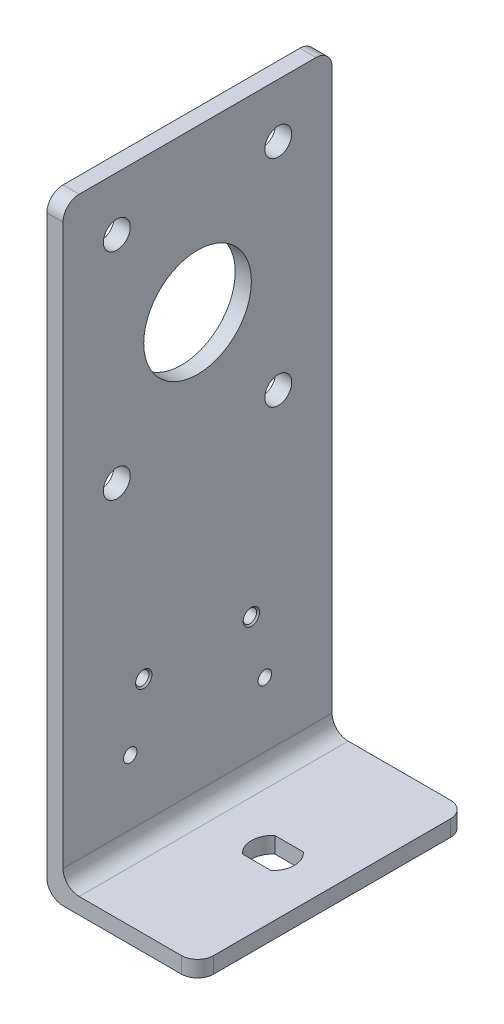
SolidWorks part; units mm, degrees
ref_plane "Front Plane" through (0, 0, 0) normal (0, 0, 1) x (1, 0, 0)
ref_plane "Top Plane" through (0, 0, 0) normal (0, 1, 0) x (1, 0, 0)
ref_plane "Right Plane" through (0, 0, 0) normal (1, 0, 0) x (0, 0, -1)
sketch "Sketch1" plane through (0, 0, 0) normal (0, 0, 1) x (1, 0, 0)
  line L0 (0, 110) -> (0, 0)
  line L1 (0, 0) -> (25, 0)
  dimension "D1" = 25
  dimension "D2" = 110
extrude "Extrude-Thin1" add sketch "Sketch1" along normal blind 50 thin
hole_wizard "Hole1" positions "3DSketch1" profile "Sketch2" legacy end condition through all
sketch3d "3DSketch1"
  line L0 (-3, 110, 50) -> (-3, 110, 0) construction
  line L1 (-3, 110, 0) -> (-3, -3, 0) construction
  point P0 (-3, 100, 10)
  point P2 (-3, 100, 40)
  point P4 (-3, 60, 40)
  point P6 (-3, 60, 10)
  dimension "D1" = 30
  dimension "D2" = 40
  dimension "D3" = 10
  dimension "D4" = 10
sketch "Sketch2" plane through (-3, 100, 10) normal (0, 1, 0) x (0, 0, 1)
  line L0 (0, 0) -> (0, 28)
  line L1 (0, 28) -> (2.5, 28)
  line L2 (2.5, 28) -> (2.5, 0)
  line L3 (2.5, 0) -> (0, 0)
  line L4 (0, 110) -> (0, -10) construction
  dimension "Diameter" = 5
  dimension "Depth" = 28
sketch "Sketch3" plane through (-3, 0, 0) normal (-1, 0, 0) x (0, 0, 1)
  line L0 (0, 110) -> (0, -3) construction
  line L1 (50, 110) -> (0, 110) construction
  circle A0 centre (25, 80) radius 10
  dimension "D3" = 20
  dimension "D1" = 25
  dimension "D2" = 30
extrude "Cut-Extrude1" cut sketch "Sketch3" against normal through all
hole_wizard "M3 Tapped Hole1" positions "3DSketch2" profile "Sketch4" tap size "M3" standard "ISO"
sketch3d "3DSketch2"
  line L0 (-3, 110, 0) -> (-3, -3, 0) construction
  line L1 (-3, 110, 50) -> (-3, 110, 0) construction
  point P0 (-3, 15, 12.5)
  point P2 (-3, 15, 37.5)
  dimension "D1" = 25
  dimension "D2" = 12.5
  dimension "D3" = 95
sketch "Sketch4" plane through (-3, 15, 12.5) normal (0, 1, 0) x (0, 0, 1)
  line L0 (0, 0) -> (0, 8.2511)
  line L1 (0, 8.2511) -> (1.25, 7.5)
  line L2 (1.25, 7.5) -> (1.25, 0.275)
  line L3 (1.25, 0.275) -> (1.525, 0)
  line L5 (1.525, 0) -> (0, 0)
  line L6 (-1.25, 0.275) -> (-1.525, 0) construction
  line L10 (0, 8.2511) -> (-1.25, 7.5) construction
  line L11 (0, -6.35) -> (0, 107.95) construction
  dimension "Tap Drill Dia." = 2.5
  dimension "Tap Drill Depth" = 7.5
  dimension "Near C'Sink Dia." = 3.05
  dimension "Near C'Sink Angle" = 90
  dimension "Drill Angle" = 118
cosmetic thread "Hole Thread1" parameters "D1"=3, "D2"=3
cosmetic thread "Hole Thread2" parameters "D1"=3, "D2"=3
sketch "Sketch5" plane through (0, -3, 0) normal (0, -1, 0) x (-1, 0, 0)
  line L0 (3, -50) -> (3, 0) construction
  line L1 (-11.3542, -22) -> (-16.6458, -22)
  line L2 (-11.3542, -28) -> (-16.6458, -28)
  line L3 (3, -50) -> (-25, -50) construction
  arc A0 (-11.3542, -28) -> (-11.3542, -22) centre (-14, -25) ccw
  arc A1 (-16.6458, -22) -> (-16.6458, -28) centre (-14, -25) ccw
  dimension "D1" = 4
  dimension "D3" = 6
  dimension "D4" = 17
  dimension "D5" = 22
extrude "Cut-Extrude2" cut sketch "Sketch5" against normal blind 10 contours L1 A1 L2 A0
fillet "Fillet1" radius 3 4 edges at (25, -1.5, 50) (25, -1.5, 0) (-1.5, 110, 0) (-1.5, 110, 50)
hole_wizard "M3 Tapped Hole2" positions "3DSketch3" profile "Sketch6" tap size "M3" standard "ISO"
sketch3d "3DSketch3"
  line L2 (0, 107, 0) -> (0, 0, 0) construction
  line L4 (0, 0, 50) -> (0, 0, 0) construction
  point P0 (0, 26, 35)
  point P2 (0, 26, 15)
  dimension "D1" = 20
  dimension "D2" = 15
  dimension "D3" = 26
sketch "Sketch6" plane through (0, 26, 35) normal (0, 1, 0) x (0, 0, -1)
  line L0 (0, 0) -> (0, 8.2511)
  line L1 (0, 8.2511) -> (1.25, 7.5)
  line L2 (1.25, 7.5) -> (1.25, 0.275)
  line L3 (1.25, 0.275) -> (1.525, 0)
  line L5 (1.525, 0) -> (0, 0)
  line L6 (-1.25, 0.275) -> (-1.525, 0) construction
  line L10 (0, 8.2511) -> (-1.25, 7.5) construction
  line L11 (0, -6.35) -> (0, 107.95) construction
  dimension "Tap Drill Dia." = 2.5
  dimension "Tap Drill Depth" = 7.5
  dimension "Near C'Sink Dia." = 3.05
  dimension "Near C'Sink Angle" = 90
  dimension "Drill Angle" = 118
cosmetic thread "Hole Thread3" parameters "D1"=3, "D2"=3
cosmetic thread "Hole Thread4" parameters "D1"=3, "D2"=3
fillet "Fillet2" radius 3 1 edges at (-3, -3, 25)
fillet "Fillet3" radius 3 1 edges at (0, 0, 25)
